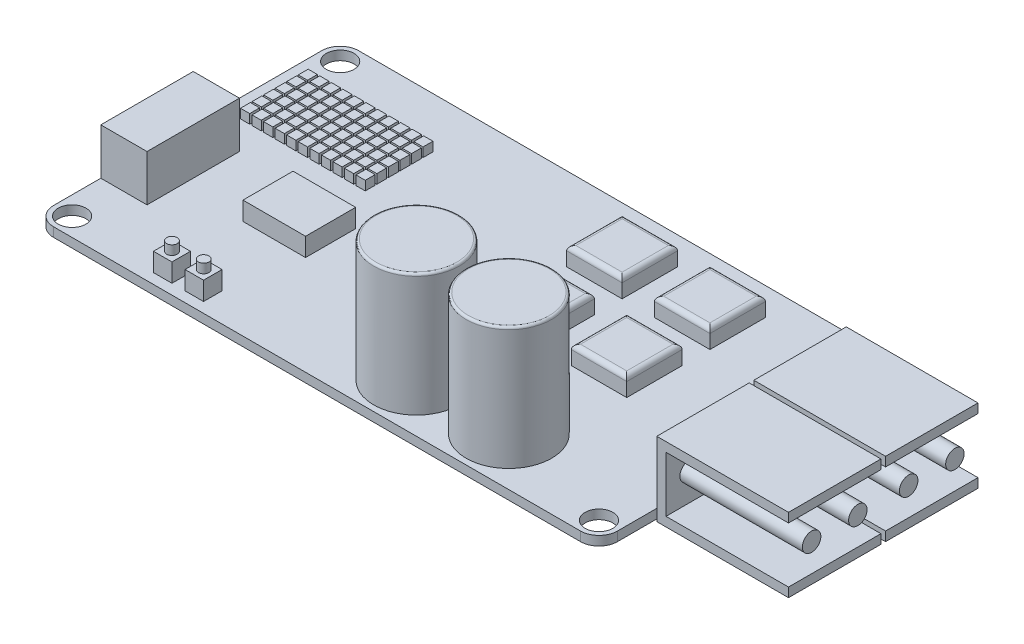
SolidWorks part; units mm, degrees
ref_plane "Front Plane" through (0, 0, 0) normal (0, 0, 1) x (1, 0, 0)
ref_plane "Top Plane" through (0, 0, 0) normal (0, 1, 0) x (1, 0, 0)
ref_plane "Right Plane" through (0, 0, 0) normal (1, 0, 0) x (0, 0, -1)
sketch "Sketch1" plane through (0, 0, 0) normal (0, 1, 0) x (1, 0, 0)
  line L1 (28.5, 16.5) -> (-28.5, 16.5)
  line L2 (30.5, 14.5) -> (30.5, -14.5)
  line L3 (28.5, -16.5) -> (-28.5, -16.5)
  line L4 (-30.5, 14.5) -> (-30.5, -14.5)
  line L5 (0, -16.5) -> (0, 16.5) construction
  line L6 (30.5, 0) -> (-30.5, 0) construction
  arc A0 (-28.5, -16.5) -> (-30.5, -14.5) centre (-28.5, -14.5) cw
  arc A1 (30.5, -14.5) -> (28.5, -16.5) centre (28.5, -14.5) cw
  arc A2 (28.5, 16.5) -> (30.5, 14.5) centre (28.5, 14.5) cw
  arc A3 (-28.5, 16.5) -> (-30.5, 14.5) centre (-28.5, 14.5) ccw
  circle A4 centre (-28.5, -14.5) radius 1.5
  circle A5 centre (28.5, -14.5) radius 1.5
  circle A6 centre (28.5, 14.5) radius 1.5
  circle A7 centre (-28.5, 14.5) radius 1.5
  point P0 (0, 0)
  point P6 (-30.5, -16.5)
  point P9 (30.5, -16.5)
  point P12 (30.5, 16.5)
  point P20 (-29.5, -15.5)
  dimension "D3" = 2
  dimension "D4" = 3
  dimension "D1" = 33
  dimension "D2" = 61
extrude "Boss-Extrude1" add sketch "Sketch1" along normal blind 1
sketch "Sketch2" plane through (0, 1, 0) normal (0, 1, 0) x (1, 0, 0)
  line L0 (-28.5, -16.5) -> (28.5, -16.5) construction
  line L1 (30.5, -14.5) -> (30.5, 14.5) construction
  circle A0 centre (15.5, -11.25) radius 4.625
  circle A1 centre (5.5, -11.25) radius 4.625
  point P8 (0, 0)
  dimension "D1" = 9.25
  dimension "D2" = 10
  dimension "D3" = 5.25
  dimension "D4" = 25
extrude "Boss-Extrude2" add sketch "Sketch2" along normal blind 13.25
fillet "Fillet1" radius 0.25 2 edges at (15.5, 14.25, 15.875) (5.5, 14.25, 15.875)
sketch "Sketch3" plane through (0, 1, 0) normal (0, 1, 0) x (1, 0, 0)
  line L0 (28.5, 16.5) -> (-28.5, 16.5) construction
  line L1 (3, 13.5) -> (9, 13.5)
  line L2 (3, 13.5) -> (3, 7.5)
  line L3 (3, 7.5) -> (9, 7.5)
  line L4 (9, 13.5) -> (9, 7.5)
  line L5 (6, 7.5) -> (6, 13.5) construction
  line L6 (3, 10.5) -> (9, 10.5) construction
  line L7 (3, 4.5) -> (9, 4.5)
  line L8 (3, 4.5) -> (3, -1.5)
  line L9 (3, -1.5) -> (9, -1.5)
  line L10 (9, 4.5) -> (9, -1.5)
  line L11 (6, -1.5) -> (6, 4.5) construction
  line L12 (3, 1.5) -> (9, 1.5) construction
  line L13 (12.5, 13.5) -> (18.5, 13.5)
  line L14 (12.5, 13.5) -> (12.5, 7.5)
  line L15 (12.5, 7.5) -> (18.5, 7.5)
  line L16 (18.5, 13.5) -> (18.5, 7.5)
  line L17 (15.5, 7.5) -> (15.5, 13.5) construction
  line L18 (12.5, 10.5) -> (18.5, 10.5) construction
  line L19 (12.5, 4.5) -> (18.5, 4.5)
  line L20 (12.5, 4.5) -> (12.5, -1.5)
  line L21 (12.5, -1.5) -> (18.5, -1.5)
  line L22 (18.5, 4.5) -> (18.5, -1.5)
  line L23 (15.5, -1.5) -> (15.5, 4.5) construction
  line L24 (12.5, 1.5) -> (18.5, 1.5) construction
  line L25 (30.5, -14.5) -> (30.5, 14.5) construction
  point P0 (6, 10.5)
  point P4 (6, 1.5)
  point P8 (15.5, 10.5)
  point P12 (15.5, 1.5)
  dimension "D1" = 6
  dimension "D2" = 6
  dimension "D3" = 9
  dimension "D4" = 9.5
  dimension "D5" = 6
  dimension "D6" = 15
extrude "Boss-Extrude3" add sketch "Sketch3" along normal blind 2
fillet "Fillet2" radius 0.5 16 edges at (6, 3, 1.5) (3, 3, -1.5) (6, 3, -4.5) (9, 3, -1.5) (15.5, 3, 1.5) (12.5, 3, -1.5) (15.5, 3, -4.5) (18.5, 3, -1.5) (15.5, 3, -7.5) (12.5, 3, -10.5) (15.5, 3, -13.5) (18.5, 3, -10.5) (6, 3, -7.5) (3, 3, -10.5) (6, 3, -13.5) (9, 3, -10.5)
sketch "Sketch4" plane through (0, 1, 0) normal (0, 1, 0) x (1, 0, 0)
  line L0 (-30.5, 14.5) -> (-30.5, -14.5) construction
  line L1 (-30.5, 0.6047) -> (-25.5, 0.6047)
  line L2 (-30.5, 0.6047) -> (-30.5, -9.3953)
  line L3 (-30.5, -9.3953) -> (-25.5, -9.3953)
  line L4 (-25.5, 0.6047) -> (-25.5, -9.3953)
  dimension "D1" = 10
  dimension "D2" = 5
extrude "Boss-Extrude4" add sketch "Sketch4" along normal blind 5 separate body
sketch "Sketch5" plane through (-30.5, 0, 0) normal (-1, 0, 0) x (0, 0, 1)
  line L0 (0.3953, 2) -> (8.3953, 2)
  line L1 (8.3953, 2) -> (8.3953, 5)
  line L2 (8.3953, 5) -> (0.3953, 5)
  line L3 (0.3953, 5) -> (0.3953, 2)
  line L4 (-0.6047, 1) -> (9.3953, 1)
  line L5 (9.3953, 1) -> (9.3953, 6)
  line L6 (9.3953, 6) -> (-0.6047, 6)
  line L7 (-0.6047, 6) -> (-0.6047, 1)
  line L8 (-0.6047, 1) -> (9.3953, 1)
  line L9 (9.3953, 1) -> (9.3953, 6)
  line L10 (9.3953, 6) -> (-0.6047, 6)
  line L11 (-0.6047, 6) -> (-0.6047, 1)
  dimension "D1" = 0
  dimension "D2" = 1
extrude "Cut-Extrude1" cut sketch "Sketch5" against normal blind 4 contours L0 L1 L2 L3
sketch "Sketch6" plane through (0, 1, 0) normal (0, 1, 0) x (1, 0, 0)
  line L0 (-30.5, 14.5) -> (-30.5, -14.5) construction
  line L1 (-28.5, 11.0357) -> (-27.5, 11.0357)
  line L2 (-28.5, 11.0357) -> (-28.5, 9.9643)
  line L3 (-28.5, 9.9643) -> (-27.5, 9.9643)
  line L4 (-27.5, 11.0357) -> (-27.5, 9.9643)
  line L5 (-28, 9.9643) -> (-28, 11.0357) construction
  line L6 (-28.5, 10.5) -> (-27.5, 10.5) construction
  line L7 (28.5, 16.5) -> (-28.5, 16.5) construction
  line L8 (-27.25, 11.0357) -> (-27.25, 9.9643)
  line L9 (-27.25, 11.0357) -> (-26.25, 11.0357)
  line L10 (-26.25, 11.0357) -> (-26.25, 9.9643)
  line L11 (-27.25, 9.9643) -> (-26.25, 9.9643)
  line L12 (-26, 11.0357) -> (-26, 9.9643)
  line L13 (-26, 11.0357) -> (-25, 11.0357)
  line L14 (-25, 11.0357) -> (-25, 9.9643)
  line L15 (-26, 9.9643) -> (-25, 9.9643)
  line L16 (-24.75, 11.0357) -> (-24.75, 9.9643)
  line L17 (-24.75, 11.0357) -> (-23.75, 11.0357)
  line L18 (-23.75, 11.0357) -> (-23.75, 9.9643)
  line L19 (-24.75, 9.9643) -> (-23.75, 9.9643)
  line L20 (-23.5, 11.0357) -> (-23.5, 9.9643)
  line L21 (-23.5, 11.0357) -> (-22.5, 11.0357)
  line L22 (-22.5, 11.0357) -> (-22.5, 9.9643)
  line L23 (-23.5, 9.9643) -> (-22.5, 9.9643)
  line L24 (-22.25, 11.0357) -> (-22.25, 9.9643)
  line L25 (-22.25, 11.0357) -> (-21.25, 11.0357)
  line L26 (-21.25, 11.0357) -> (-21.25, 9.9643)
  line L27 (-22.25, 9.9643) -> (-21.25, 9.9643)
  line L28 (-21, 11.0357) -> (-21, 9.9643)
  line L29 (-21, 11.0357) -> (-20, 11.0357)
  line L30 (-20, 11.0357) -> (-20, 9.9643)
  line L31 (-21, 9.9643) -> (-20, 9.9643)
  line L32 (-19.75, 11.0357) -> (-19.75, 9.9643)
  line L33 (-19.75, 11.0357) -> (-18.75, 11.0357)
  line L34 (-18.75, 11.0357) -> (-18.75, 9.9643)
  line L35 (-19.75, 9.9643) -> (-18.75, 9.9643)
  line L36 (-18.5, 11.0357) -> (-18.5, 9.9643)
  line L37 (-18.5, 11.0357) -> (-17.5, 11.0357)
  line L38 (-17.5, 11.0357) -> (-17.5, 9.9643)
  line L39 (-18.5, 9.9643) -> (-17.5, 9.9643)
  line L40 (-17.25, 11.0357) -> (-17.25, 9.9643)
  line L41 (-17.25, 11.0357) -> (-16.25, 11.0357)
  line L42 (-16.25, 11.0357) -> (-16.25, 9.9643)
  line L43 (-17.25, 9.9643) -> (-16.25, 9.9643)
  line L44 (-16, 11.0357) -> (-16, 9.9643)
  line L45 (-16, 11.0357) -> (-15, 11.0357)
  line L46 (-15, 11.0357) -> (-15, 9.9643)
  line L47 (-16, 9.9643) -> (-15, 9.9643)
  line L48 (-16, 9.7857) -> (-16, 8.7143)
  line L49 (-16, 8.7143) -> (-15, 8.7143)
  line L50 (-15, 9.7857) -> (-15, 8.7143)
  line L51 (-16, 9.7857) -> (-15, 9.7857)
  line L52 (-17.25, 9.7857) -> (-17.25, 8.7143)
  line L53 (-17.25, 8.7143) -> (-16.25, 8.7143)
  line L54 (-16.25, 9.7857) -> (-16.25, 8.7143)
  line L55 (-17.25, 9.7857) -> (-16.25, 9.7857)
  line L56 (-18.5, 9.7857) -> (-18.5, 8.7143)
  line L57 (-18.5, 8.7143) -> (-17.5, 8.7143)
  line L58 (-17.5, 9.7857) -> (-17.5, 8.7143)
  line L59 (-18.5, 9.7857) -> (-17.5, 9.7857)
  line L60 (-19.75, 9.7857) -> (-19.75, 8.7143)
  line L61 (-19.75, 8.7143) -> (-18.75, 8.7143)
  line L62 (-18.75, 9.7857) -> (-18.75, 8.7143)
  line L63 (-19.75, 9.7857) -> (-18.75, 9.7857)
  line L64 (-21, 9.7857) -> (-21, 8.7143)
  line L65 (-21, 8.7143) -> (-20, 8.7143)
  line L66 (-20, 9.7857) -> (-20, 8.7143)
  line L67 (-21, 9.7857) -> (-20, 9.7857)
  line L68 (-22.25, 9.7857) -> (-22.25, 8.7143)
  line L69 (-22.25, 8.7143) -> (-21.25, 8.7143)
  line L70 (-21.25, 9.7857) -> (-21.25, 8.7143)
  line L71 (-22.25, 9.7857) -> (-21.25, 9.7857)
  line L72 (-23.5, 9.7857) -> (-23.5, 8.7143)
  line L73 (-23.5, 8.7143) -> (-22.5, 8.7143)
  line L74 (-22.5, 9.7857) -> (-22.5, 8.7143)
  line L75 (-23.5, 9.7857) -> (-22.5, 9.7857)
  line L76 (-24.75, 9.7857) -> (-24.75, 8.7143)
  line L77 (-24.75, 8.7143) -> (-23.75, 8.7143)
  line L78 (-23.75, 9.7857) -> (-23.75, 8.7143)
  line L79 (-24.75, 9.7857) -> (-23.75, 9.7857)
  line L80 (-26, 9.7857) -> (-26, 8.7143)
  line L81 (-26, 8.7143) -> (-25, 8.7143)
  line L82 (-25, 9.7857) -> (-25, 8.7143)
  line L83 (-26, 9.7857) -> (-25, 9.7857)
  line L84 (-27.25, 9.7857) -> (-27.25, 8.7143)
  line L85 (-27.25, 8.7143) -> (-26.25, 8.7143)
  line L86 (-26.25, 9.7857) -> (-26.25, 8.7143)
  line L87 (-27.25, 9.7857) -> (-26.25, 9.7857)
  line L88 (-28.5, 9.7857) -> (-28.5, 8.7143)
  line L89 (-28.5, 9.7857) -> (-27.5, 9.7857)
  line L90 (-27.5, 9.7857) -> (-27.5, 8.7143)
  line L91 (-28.5, 8.7143) -> (-27.5, 8.7143)
  line L92 (-16, 8.5357) -> (-16, 7.4643)
  line L93 (-16, 7.4643) -> (-15, 7.4643)
  line L94 (-15, 8.5357) -> (-15, 7.4643)
  line L95 (-16, 8.5357) -> (-15, 8.5357)
  line L96 (-17.25, 8.5357) -> (-17.25, 7.4643)
  line L97 (-17.25, 7.4643) -> (-16.25, 7.4643)
  line L98 (-16.25, 8.5357) -> (-16.25, 7.4643)
  line L99 (-17.25, 8.5357) -> (-16.25, 8.5357)
  line L100 (-18.5, 8.5357) -> (-18.5, 7.4643)
  line L101 (-18.5, 7.4643) -> (-17.5, 7.4643)
  line L102 (-17.5, 8.5357) -> (-17.5, 7.4643)
  line L103 (-18.5, 8.5357) -> (-17.5, 8.5357)
  line L104 (-19.75, 8.5357) -> (-19.75, 7.4643)
  line L105 (-19.75, 7.4643) -> (-18.75, 7.4643)
  line L106 (-18.75, 8.5357) -> (-18.75, 7.4643)
  line L107 (-19.75, 8.5357) -> (-18.75, 8.5357)
  line L108 (-21, 8.5357) -> (-21, 7.4643)
  line L109 (-21, 7.4643) -> (-20, 7.4643)
  line L110 (-20, 8.5357) -> (-20, 7.4643)
  line L111 (-21, 8.5357) -> (-20, 8.5357)
  line L112 (-22.25, 8.5357) -> (-22.25, 7.4643)
  line L113 (-22.25, 7.4643) -> (-21.25, 7.4643)
  line L114 (-21.25, 8.5357) -> (-21.25, 7.4643)
  line L115 (-22.25, 8.5357) -> (-21.25, 8.5357)
  line L116 (-23.5, 8.5357) -> (-23.5, 7.4643)
  line L117 (-23.5, 7.4643) -> (-22.5, 7.4643)
  line L118 (-22.5, 8.5357) -> (-22.5, 7.4643)
  line L119 (-23.5, 8.5357) -> (-22.5, 8.5357)
  line L120 (-24.75, 8.5357) -> (-24.75, 7.4643)
  line L121 (-24.75, 7.4643) -> (-23.75, 7.4643)
  line L122 (-23.75, 8.5357) -> (-23.75, 7.4643)
  line L123 (-24.75, 8.5357) -> (-23.75, 8.5357)
  line L124 (-26, 8.5357) -> (-26, 7.4643)
  line L125 (-26, 7.4643) -> (-25, 7.4643)
  line L126 (-25, 8.5357) -> (-25, 7.4643)
  line L127 (-26, 8.5357) -> (-25, 8.5357)
  line L128 (-27.25, 8.5357) -> (-27.25, 7.4643)
  line L129 (-27.25, 7.4643) -> (-26.25, 7.4643)
  line L130 (-26.25, 8.5357) -> (-26.25, 7.4643)
  line L131 (-27.25, 8.5357) -> (-26.25, 8.5357)
  line L132 (-28.5, 8.5357) -> (-28.5, 7.4643)
  line L133 (-28.5, 8.5357) -> (-27.5, 8.5357)
  line L134 (-27.5, 8.5357) -> (-27.5, 7.4643)
  line L135 (-28.5, 7.4643) -> (-27.5, 7.4643)
  line L136 (-16, 7.2857) -> (-16, 6.2143)
  line L137 (-16, 6.2143) -> (-15, 6.2143)
  line L138 (-15, 7.2857) -> (-15, 6.2143)
  line L139 (-16, 7.2857) -> (-15, 7.2857)
  line L140 (-17.25, 7.2857) -> (-17.25, 6.2143)
  line L141 (-17.25, 6.2143) -> (-16.25, 6.2143)
  line L142 (-16.25, 7.2857) -> (-16.25, 6.2143)
  line L143 (-17.25, 7.2857) -> (-16.25, 7.2857)
  line L144 (-18.5, 7.2857) -> (-18.5, 6.2143)
  line L145 (-18.5, 6.2143) -> (-17.5, 6.2143)
  line L146 (-17.5, 7.2857) -> (-17.5, 6.2143)
  line L147 (-18.5, 7.2857) -> (-17.5, 7.2857)
  line L148 (-19.75, 7.2857) -> (-19.75, 6.2143)
  line L149 (-19.75, 6.2143) -> (-18.75, 6.2143)
  line L150 (-18.75, 7.2857) -> (-18.75, 6.2143)
  line L151 (-19.75, 7.2857) -> (-18.75, 7.2857)
  line L152 (-21, 7.2857) -> (-21, 6.2143)
  line L153 (-21, 6.2143) -> (-20, 6.2143)
  line L154 (-20, 7.2857) -> (-20, 6.2143)
  line L155 (-21, 7.2857) -> (-20, 7.2857)
  line L156 (-22.25, 7.2857) -> (-22.25, 6.2143)
  line L157 (-22.25, 6.2143) -> (-21.25, 6.2143)
  line L158 (-21.25, 7.2857) -> (-21.25, 6.2143)
  line L159 (-22.25, 7.2857) -> (-21.25, 7.2857)
  line L160 (-23.5, 7.2857) -> (-23.5, 6.2143)
  line L161 (-23.5, 6.2143) -> (-22.5, 6.2143)
  line L162 (-22.5, 7.2857) -> (-22.5, 6.2143)
  line L163 (-23.5, 7.2857) -> (-22.5, 7.2857)
  line L164 (-24.75, 7.2857) -> (-24.75, 6.2143)
  line L165 (-24.75, 6.2143) -> (-23.75, 6.2143)
  line L166 (-23.75, 7.2857) -> (-23.75, 6.2143)
  line L167 (-24.75, 7.2857) -> (-23.75, 7.2857)
  line L168 (-26, 7.2857) -> (-26, 6.2143)
  line L169 (-26, 6.2143) -> (-25, 6.2143)
  line L170 (-25, 7.2857) -> (-25, 6.2143)
  line L171 (-26, 7.2857) -> (-25, 7.2857)
  line L172 (-27.25, 7.2857) -> (-27.25, 6.2143)
  line L173 (-27.25, 6.2143) -> (-26.25, 6.2143)
  line L174 (-26.25, 7.2857) -> (-26.25, 6.2143)
  line L175 (-27.25, 7.2857) -> (-26.25, 7.2857)
  line L176 (-28.5, 7.2857) -> (-28.5, 6.2143)
  line L177 (-28.5, 7.2857) -> (-27.5, 7.2857)
  line L178 (-27.5, 7.2857) -> (-27.5, 6.2143)
  line L179 (-28.5, 6.2143) -> (-27.5, 6.2143)
  line L180 (-16, 6.0357) -> (-16, 4.9643)
  line L181 (-16, 4.9643) -> (-15, 4.9643)
  line L182 (-15, 6.0357) -> (-15, 4.9643)
  line L183 (-16, 6.0357) -> (-15, 6.0357)
  line L184 (-17.25, 6.0357) -> (-17.25, 4.9643)
  line L185 (-17.25, 4.9643) -> (-16.25, 4.9643)
  line L186 (-16.25, 6.0357) -> (-16.25, 4.9643)
  line L187 (-17.25, 6.0357) -> (-16.25, 6.0357)
  line L188 (-18.5, 6.0357) -> (-18.5, 4.9643)
  line L189 (-18.5, 4.9643) -> (-17.5, 4.9643)
  line L190 (-17.5, 6.0357) -> (-17.5, 4.9643)
  line L191 (-18.5, 6.0357) -> (-17.5, 6.0357)
  line L192 (-19.75, 6.0357) -> (-19.75, 4.9643)
  line L193 (-19.75, 4.9643) -> (-18.75, 4.9643)
  line L194 (-18.75, 6.0357) -> (-18.75, 4.9643)
  line L195 (-19.75, 6.0357) -> (-18.75, 6.0357)
  line L196 (-21, 6.0357) -> (-21, 4.9643)
  line L197 (-21, 4.9643) -> (-20, 4.9643)
  line L198 (-20, 6.0357) -> (-20, 4.9643)
  line L199 (-21, 6.0357) -> (-20, 6.0357)
  line L200 (-22.25, 6.0357) -> (-22.25, 4.9643)
  line L201 (-22.25, 4.9643) -> (-21.25, 4.9643)
  line L202 (-21.25, 6.0357) -> (-21.25, 4.9643)
  line L203 (-22.25, 6.0357) -> (-21.25, 6.0357)
  line L204 (-23.5, 6.0357) -> (-23.5, 4.9643)
  line L205 (-23.5, 4.9643) -> (-22.5, 4.9643)
  line L206 (-22.5, 6.0357) -> (-22.5, 4.9643)
  line L207 (-23.5, 6.0357) -> (-22.5, 6.0357)
  line L208 (-24.75, 6.0357) -> (-24.75, 4.9643)
  line L209 (-24.75, 4.9643) -> (-23.75, 4.9643)
  line L210 (-23.75, 6.0357) -> (-23.75, 4.9643)
  line L211 (-24.75, 6.0357) -> (-23.75, 6.0357)
  line L212 (-26, 6.0357) -> (-26, 4.9643)
  line L213 (-26, 4.9643) -> (-25, 4.9643)
  line L214 (-25, 6.0357) -> (-25, 4.9643)
  line L215 (-26, 6.0357) -> (-25, 6.0357)
  line L216 (-27.25, 6.0357) -> (-27.25, 4.9643)
  line L217 (-27.25, 4.9643) -> (-26.25, 4.9643)
  line L218 (-26.25, 6.0357) -> (-26.25, 4.9643)
  line L219 (-27.25, 6.0357) -> (-26.25, 6.0357)
  line L220 (-28.5, 6.0357) -> (-28.5, 4.9643)
  line L221 (-28.5, 6.0357) -> (-27.5, 6.0357)
  line L222 (-27.5, 6.0357) -> (-27.5, 4.9643)
  line L223 (-28.5, 4.9643) -> (-27.5, 4.9643)
  line L224 (-16, 4.7857) -> (-16, 3.7143)
  line L225 (-16, 3.7143) -> (-15, 3.7143)
  line L226 (-15, 4.7857) -> (-15, 3.7143)
  line L227 (-16, 4.7857) -> (-15, 4.7857)
  line L228 (-17.25, 4.7857) -> (-17.25, 3.7143)
  line L229 (-17.25, 3.7143) -> (-16.25, 3.7143)
  line L230 (-16.25, 4.7857) -> (-16.25, 3.7143)
  line L231 (-17.25, 4.7857) -> (-16.25, 4.7857)
  line L232 (-18.5, 4.7857) -> (-18.5, 3.7143)
  line L233 (-18.5, 3.7143) -> (-17.5, 3.7143)
  line L234 (-17.5, 4.7857) -> (-17.5, 3.7143)
  line L235 (-18.5, 4.7857) -> (-17.5, 4.7857)
  line L236 (-19.75, 4.7857) -> (-19.75, 3.7143)
  line L237 (-19.75, 3.7143) -> (-18.75, 3.7143)
  line L238 (-18.75, 4.7857) -> (-18.75, 3.7143)
  line L239 (-19.75, 4.7857) -> (-18.75, 4.7857)
  line L240 (-21, 4.7857) -> (-21, 3.7143)
  line L241 (-21, 3.7143) -> (-20, 3.7143)
  line L242 (-20, 4.7857) -> (-20, 3.7143)
  line L243 (-21, 4.7857) -> (-20, 4.7857)
  line L244 (-22.25, 4.7857) -> (-22.25, 3.7143)
  line L245 (-22.25, 3.7143) -> (-21.25, 3.7143)
  line L246 (-21.25, 4.7857) -> (-21.25, 3.7143)
  line L247 (-22.25, 4.7857) -> (-21.25, 4.7857)
  line L248 (-23.5, 4.7857) -> (-23.5, 3.7143)
  line L249 (-23.5, 3.7143) -> (-22.5, 3.7143)
  line L250 (-22.5, 4.7857) -> (-22.5, 3.7143)
  line L251 (-23.5, 4.7857) -> (-22.5, 4.7857)
  line L252 (-24.75, 4.7857) -> (-24.75, 3.7143)
  line L253 (-24.75, 3.7143) -> (-23.75, 3.7143)
  line L254 (-23.75, 4.7857) -> (-23.75, 3.7143)
  line L255 (-24.75, 4.7857) -> (-23.75, 4.7857)
  line L256 (-26, 4.7857) -> (-26, 3.7143)
  line L257 (-26, 3.7143) -> (-25, 3.7143)
  line L258 (-25, 4.7857) -> (-25, 3.7143)
  line L259 (-26, 4.7857) -> (-25, 4.7857)
  line L260 (-27.25, 4.7857) -> (-27.25, 3.7143)
  line L261 (-27.25, 3.7143) -> (-26.25, 3.7143)
  line L262 (-26.25, 4.7857) -> (-26.25, 3.7143)
  line L263 (-27.25, 4.7857) -> (-26.25, 4.7857)
  line L264 (-28.5, 4.7857) -> (-28.5, 3.7143)
  line L265 (-28.5, 4.7857) -> (-27.5, 4.7857)
  line L266 (-27.5, 4.7857) -> (-27.5, 3.7143)
  line L267 (-28.5, 3.7143) -> (-27.5, 3.7143)
  point P0 (-28, 10.5)
  dimension "D1" = 1
  dimension "D2" = 1.0714
  dimension "D3" = 2
  dimension "D4" = 6
  dimension "D5" = 11
  dimension "D6" = 6
extrude "Boss-Extrude5" add sketch "Sketch6" along normal blind 1
sketch "Sketch7" plane through (0, 1, 0) normal (0, 1, 0) x (1, 0, 0)
  line L1 (-18.76, -0.3386) -> (-11.9874, -0.3386)
  line L2 (-18.76, -0.3386) -> (-18.76, -5.7567)
  line L3 (-18.76, -5.7567) -> (-11.9874, -5.7567)
  line L4 (-11.9874, -0.3386) -> (-11.9874, -5.7567)
  line L5 (-15.3737, -5.7567) -> (-15.3737, -0.3386) construction
  line L6 (-18.76, -3.0477) -> (-11.9874, -3.0477) construction
  point P0 (-15.3737, -3.0477)
extrude "Boss-Extrude6" add sketch "Sketch7" along normal blind 2
sketch "Sketch9" plane through (30.5, 0, 0) normal (1, 0, 0) x (0, 0, -1)
  line L0 (0, 0) -> (0, -6.1717) construction
  line L1 (-0.25, 7.75) -> (-10.25, 7.75)
  line L2 (-0.25, 7.75) -> (-0.25, -0.25)
  line L3 (-0.25, -0.25) -> (-10.25, -0.25)
  line L4 (-10.25, 7.75) -> (-10.25, -0.25)
  line L5 (-5.25, -0.25) -> (-5.25, 7.75) construction
  line L6 (-0.25, 3.75) -> (-10.25, 3.75) construction
  line L7 (-14.5, 0) -> (14.5, 0) construction
  line L8 (0.25, -0.25) -> (10.25, -0.25)
  line L9 (10.25, 7.75) -> (10.25, -0.25)
  line L10 (0.25, 7.75) -> (10.25, 7.75)
  line L11 (0.25, 7.75) -> (0.25, -0.25)
  point P0 (-5.25, 3.75)
  dimension "D1" = 10
  dimension "D2" = 0.25
  dimension "D3" = 0.25
  dimension "D4" = 8
extrude "Boss-Extrude7" add sketch "Sketch9" along normal blind 1 separate body
sketch "Sketch10" plane through (31.5, 0, 0) normal (1, 0, 0) x (0, 0, -1)
  line L0 (-0.25, -0.25) -> (-0.25, 7.75) construction
  line L1 (-10.25, 7.75) -> (-0.25, 7.75)
  line L2 (-10.25, 7.75) -> (-10.25, 6.75)
  line L3 (-10.25, 6.75) -> (-0.25, 6.75)
  line L4 (-0.25, 7.75) -> (-0.25, 6.75)
  line L5 (0, 0) -> (0, -3.2221) construction
  line L6 (-10.25, -0.25) -> (-0.25, -0.25)
  line L7 (-10.25, -0.25) -> (-10.25, 0.75)
  line L8 (-10.25, 0.75) -> (-0.25, 0.75)
  line L9 (-0.25, -0.25) -> (-0.25, 0.75)
  line L10 (10.25, 6.75) -> (0.25, 6.75)
  line L11 (0.25, 7.75) -> (0.25, 6.75)
  line L12 (10.25, 7.75) -> (0.25, 7.75)
  line L13 (10.25, 7.75) -> (10.25, 6.75)
  line L14 (10.25, 0.75) -> (0.25, 0.75)
  line L15 (0.25, -0.25) -> (0.25, 0.75)
  line L16 (10.25, -0.25) -> (0.25, -0.25)
  line L17 (10.25, -0.25) -> (10.25, 0.75)
  dimension "D1" = 1
extrude "Boss-Extrude8" add sketch "Sketch10" along normal blind 13.25
sketch "Sketch11" plane through (31.5, 0, 0) normal (1, 0, 0) x (0, 0, -1)
  line L0 (0, 0) -> (0, -2.2126) construction
  line L1 (-5.25, -0.25) -> (-5.25, 2.8607) construction
  line L2 (-10.25, -0.25) -> (-0.25, -0.25) construction
  circle A0 centre (-7.75, 3.7488) radius 1
  circle A1 centre (-2.75, 3.7488) radius 1
  circle A2 centre (2.75, 3.7488) radius 1
  circle A3 centre (7.75, 3.7488) radius 1
  point P8 (0, 0)
  dimension "D1" = 2
  dimension "D2" = 5
  dimension "D3" = 5
extrude "Boss-Extrude9" add sketch "Sketch11" along normal up to surface (13.25 mm away)
sketch "Sketch12" plane through (0, 1, 0) normal (0, 1, 0) x (1, 0, 0)
  line L1 (-18.8068, -13.3911) -> (-16.8068, -13.3911)
  line L2 (-18.8068, -13.3911) -> (-18.8068, -15.3911)
  line L3 (-18.8068, -15.3911) -> (-16.8068, -15.3911)
  line L4 (-16.8068, -13.3911) -> (-16.8068, -15.3911)
  line L5 (-17.8068, -15.3911) -> (-17.8068, -13.3911) construction
  line L6 (-18.8068, -14.3911) -> (-16.8068, -14.3911) construction
  line L7 (-15.3896, -13.3911) -> (-13.3896, -13.3911)
  line L8 (-15.3896, -13.3911) -> (-15.3896, -15.3911)
  line L9 (-15.3896, -15.3911) -> (-13.3896, -15.3911)
  line L10 (-13.3896, -13.3911) -> (-13.3896, -15.3911)
  line L11 (-14.3896, -15.3911) -> (-14.3896, -13.3911) construction
  line L12 (-15.3896, -14.3911) -> (-13.3896, -14.3911) construction
  point P0 (-17.8068, -14.3911)
  point P4 (-14.3896, -14.3911)
  dimension "D1" = 2
  dimension "D2" = 2
extrude "Boss-Extrude10" add sketch "Sketch12" along normal blind 2
sketch "Sketch13" plane through (0, 3, 0) normal (0, 1, 0) x (1, 0, 0)
  circle A0 centre (-17.8068, -14.3911) radius 0.5669
  circle A1 centre (-14.3699, -14.3911) radius 0.5669
extrude "Boss-Extrude11" add sketch "Sketch13" along normal blind 1 contours A0 | A1
